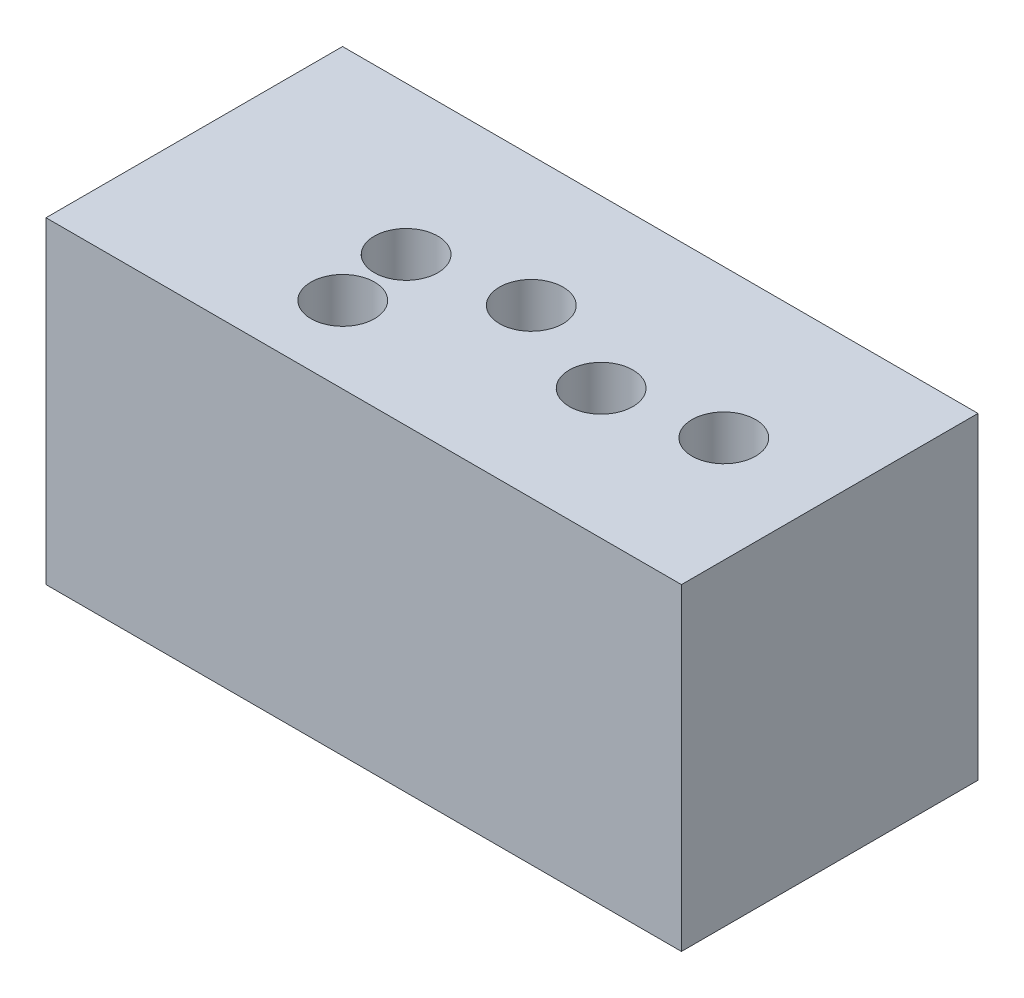
SolidWorks part; units mm, degrees
ref_plane "Front Plane" through (0, 0, 0) normal (0, 0, 1) x (1, 0, 0)
ref_plane "Top Plane" through (0, 0, 0) normal (0, 1, 0) x (1, 0, 0)
ref_plane "Right Plane" through (0, 0, 0) normal (1, 0, 0) x (0, 0, -1)
sketch "Sketch1" plane through (0, 0, 0) normal (0, 1, 0) x (1, 0, 0)
  line L1 (0, 0) -> (38.1, 0)
  line L2 (0, 0) -> (0, 17.78)
  line L3 (0, 17.78) -> (38.1, 17.78)
  line L4 (38.1, 0) -> (38.1, 17.78)
  dimension "D1" = 17.78
  dimension "D2" = 38.1
extrude "Boss-Extrude1" add sketch "Sketch1" along normal mid plane 19.05
sketch "Sketch2" plane through (0, 9.525, 0) normal (0, 1, 0) x (1, 0, 0)
  line L0 (38.1, 8.89) -> (0, 8.89) construction
  line L1 (38.1, 0) -> (38.1, 17.78) construction
  line L2 (0, 17.78) -> (0, 0) construction
  line L3 (19.0983, 9.9969) -> (31.75, 8.89) construction
  line L4 (31.75, 8.89) -> (25.4965, 7.7873) construction
  line L5 (31.75, 8.89) -> (13.1883, 4.6047) construction
  circle A0 centre (31.75, 8.89) radius 1.905
  circle A1 centre (19.0983, 9.9969) radius 1.905
  circle A2 centre (12.7, 8.89) radius 1.905
  circle A3 centre (25.4965, 7.7873) radius 1.905
  circle A12 centre (13.1883, 4.6047) radius 1.905
  point P10 (0, 0)
  dimension "D1" = 3.81
  dimension "D9" = 13
  dimension "D2" = 12.7
  dimension "D3" = 19.05
  dimension "D4" = 6.35
  dimension "D5" = 6.35
  dimension "D6" = 5
  dimension "D7" = 10
  dimension "D8" = 19.05
extrude "Cut-Extrude1" cut sketch "Sketch2" against normal blind 12.7
